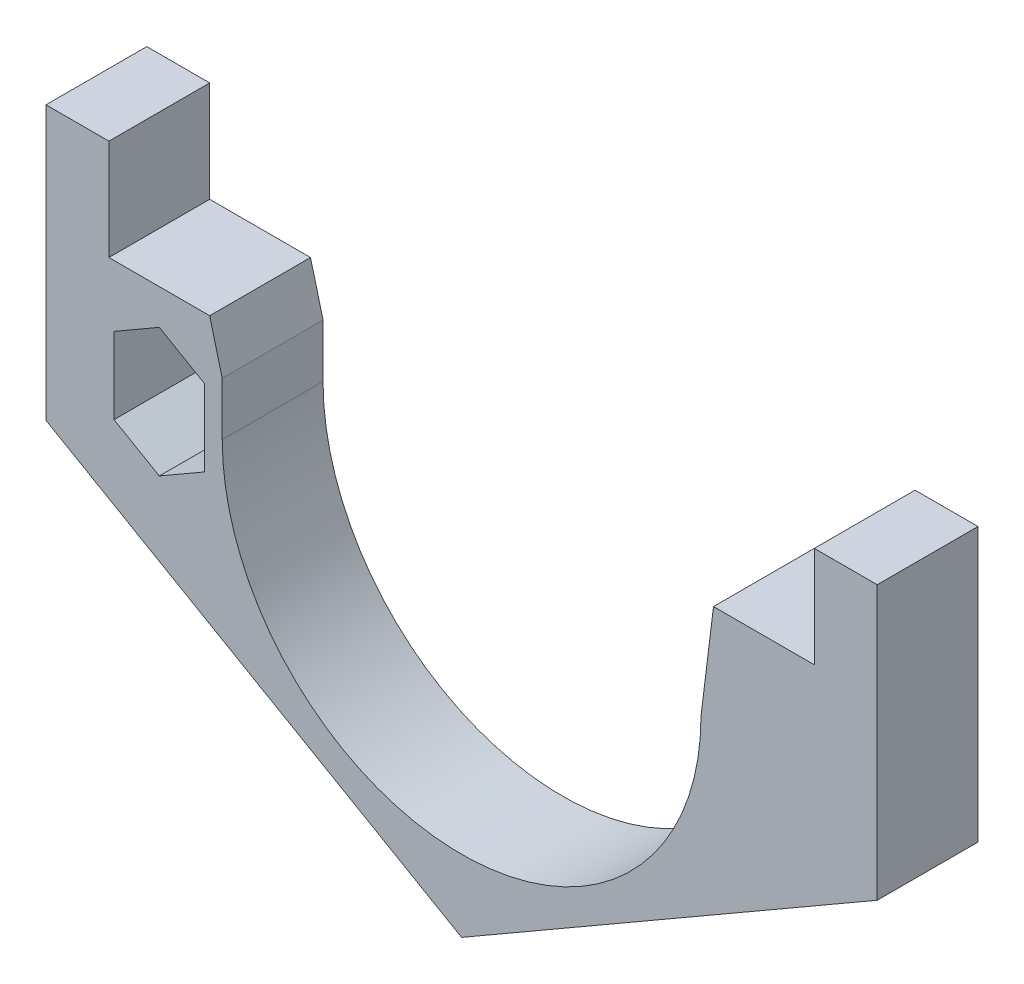
SolidWorks part; units mm, degrees
ref_plane "Front" through (0, 0, 0) normal (0, 0, 1) x (1, 0, 0)
ref_plane "Top" through (0, 0, 0) normal (0, 1, 0) x (1, 0, 0)
ref_plane "Right" through (0, 0, 0) normal (1, 0, 0) x (0, 0, -1)
sketch "Skizze1" plane through (0, 0, 0) normal (0, 0, 1) x (1, 0, 0)
  line L0 (-49.9845, 20.069) -> (-69.9845, 20.069)
  line L3 (0, 0) -> (0, -130.7529) construction
  line L6 (49.9845, 20.069) -> (69.9845, 20.069)
  line L8 (49.9845, 20.069) -> (47.5, 0)
  line L10 (-69.9845, 40.069) -> (-82.4684, 40.069)
  line L11 (-82.4684, 40.069) -> (-82.4684, -2.9373)
  line L12 (-69.9845, 200.069) -> (-69.9845, -99.931) construction
  line L13 (-69.9845, 20.069) -> (-69.9845, 40.069)
  line L14 (69.9845, 20.069) -> (69.9845, 40.069)
  line L15 (82.4684, 40.069) -> (82.4684, -2.9373)
  line L16 (69.9845, 40.069) -> (82.4684, 40.069)
  line L17 (0, -2.9373) -> (109.2749, -2.9373) construction
  line L18 (0, -61.7765) -> (82.4684, -14.1634)
  line L19 (82.4684, -14.1634) -> (82.4684, -2.9373)
  line L20 (-82.4684, -14.1634) -> (-82.4684, -2.9373)
  line L21 (0, -61.7765) -> (-82.4684, -14.1634)
  line L22 (-59.9845, 20.069) -> (-59.9845, -34.272) construction
  line L23 (-59.9845, -99.931) -> (-59.9845, 200.069) construction
  line L24 (-59.9845, 0.2978) -> (-41.7529, 0.2978) construction
  line L25 (-59.9845, 13.069) -> (-51, 7.8818)
  line L26 (-51, 7.8818) -> (-51, -7.2862)
  line L27 (-59.9845, -12.4734) -> (-51, -7.2862)
  line L28 (-59.9845, -12.4734) -> (-68.9689, -7.2862)
  line L29 (-68.9689, 7.8818) -> (-68.9689, -7.2862)
  line L30 (-59.9845, 13.069) -> (-68.9689, 7.8818)
  line L37 (-47.5, 0) -> (-47.5, 10.569)
  line L38 (-47.5, 10.569) -> (-49.9845, 20.069)
  arc A0 (-47.5, 0) -> (47.5, 0) centre (0, 0) ccw
  point P37 (-51, 0.2978)
  dimension "D1" = 12.4839
  dimension "D3" = 53.5
  dimension "D2" = 120
  dimension "D4" = 120
  dimension "D5" = 7
  dimension "D6" = 3.5
  dimension "D9" = 9.5
extrude "Aufsatz-Linear austragen1" add sketch "Skizze1" along normal blind 20
